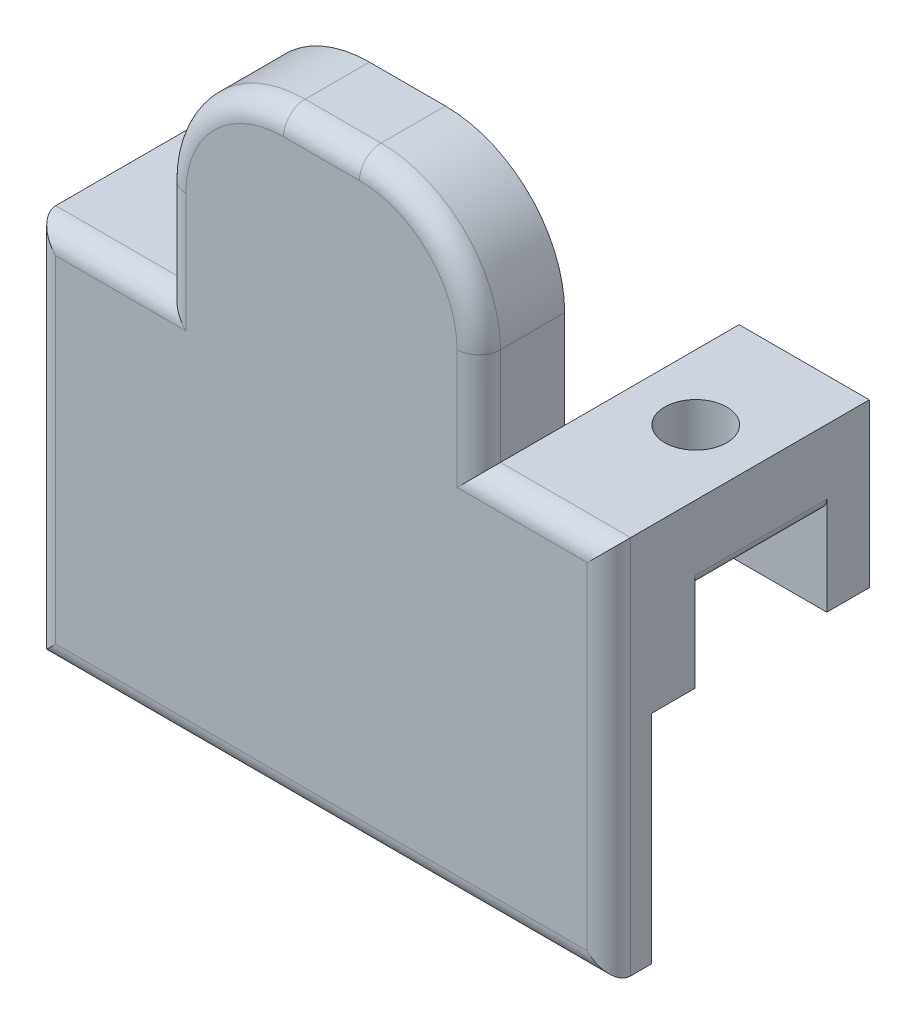
SolidWorks part; units mm, degrees
material "아크릴(내충격성)"
ref_plane "정면" through (0, 0, 0) normal (0, 0, 1) x (1, 0, 0)
ref_plane "윗면" through (0, 0, 0) normal (0, 1, 0) x (1, 0, 0)
ref_plane "우측면" through (0, 0, 0) normal (1, 0, 0) x (0, 0, -1)
sketch "스케치1" plane through (0, 0, 0) normal (0, 0, 1) x (1, 0, 0)
  line L1 (-26.5, 17.5) -> (26.5, 17.5)
  line L2 (-26.5, 17.5) -> (-26.5, -17.5)
  line L3 (-26.5, -17.5) -> (26.5, -17.5)
  line L4 (26.5, 17.5) -> (26.5, -17.5)
  line L5 (-26.5, 17.5) -> (26.5, -17.5) construction
  line L6 (-26.5, -17.5) -> (26.5, 17.5) construction
  point P0 (0, 0)
  dimension "D1" = 35
  dimension "D2" = 53
extrude "보스-돌출1" add sketch "스케치1" along normal blind 3.92
sketch "스케치2" plane through (0, 0, 3.92) normal (0, 0, 1) x (1, 0, 0)
  line L0 (26.5, 17.5) -> (-26.5, 17.5) construction
  line L1 (-26.5, 17.5) -> (-14.5, 17.5)
  line L2 (-26.5, 17.5) -> (-26.5, -9.5)
  line L3 (-26.5, -9.5) -> (-14.5, -9.5)
  line L4 (-14.5, 17.5) -> (-14.5, -9.5)
  line L5 (14.5, 17.5) -> (26.5, 17.5)
  line L6 (14.5, 17.5) -> (14.5, -9.5)
  line L7 (14.5, -9.5) -> (26.5, -9.5)
  line L8 (26.5, 17.5) -> (26.5, -9.5)
  line L9 (26.5, -17.5) -> (26.5, 17.5) construction
  dimension "D1" = 27
  dimension "D2" = 12
  dimension "D3" = 12
  dimension "D4" = 27
extrude "컷-돌출1" cut sketch "스케치2" against normal blind 4
sketch "스케치3" plane through (0, 0, 0) normal (0, 0, -1) x (-1, 0, 0)
  line L0 (0, 11) -> (0, -11) construction
  line L1 (-14.5, -9.5) -> (-26.5, -9.5)
  line L2 (-14.5, -9.5) -> (-14.5, -2.5)
  line L3 (-14.5, -2.5) -> (-26.5, -2.5)
  line L4 (-26.5, -9.5) -> (-26.5, -2.5)
  line L5 (26.5, -9.5) -> (26.5, -2.5)
  line L6 (14.5, -2.5) -> (26.5, -2.5)
  line L7 (14.5, -9.5) -> (14.5, -2.5)
  line L8 (14.5, -9.5) -> (26.5, -9.5)
  dimension "D1" = 12
  dimension "D2" = 7
extrude "보스-돌출2" add sketch "스케치3" along normal blind 16.08 and the other way through all
sketch "스케치4" plane through (0, -9.5, 0) normal (0, -1, 0) x (1, 0, 0)
  line L0 (-14.5, 0) -> (-14.5, -16.08) construction
  line L1 (-26.5, -16.08) -> (-14.5, -16.08)
  line L2 (-26.5, -16.08) -> (-26.5, -12.16)
  line L3 (-26.5, -12.16) -> (-14.5, -12.16)
  line L4 (-14.5, -16.08) -> (-14.5, -12.16)
  line L5 (26.5, -16.08) -> (14.5, -16.08) construction
  line L6 (14.5, -16.08) -> (26.5, -16.08)
  line L7 (14.5, -16.08) -> (14.5, -12.16)
  line L8 (14.5, -12.16) -> (26.5, -12.16)
  line L9 (26.5, -16.08) -> (26.5, -12.16)
  line L10 (26.5, 0) -> (26.5, -16.08) construction
  dimension "D1" = 3.92
  dimension "D2" = 3.92
extrude "보스-돌출3" add sketch "스케치4" along normal blind 8
sketch "스케치5" plane through (0, -2.5, 0) normal (0, 1, 0) x (1, 0, 0)
  line L0 (-26.5, -3.92) -> (-26.5, 16.08) construction
  line L1 (-26.5, -3.92) -> (-14.5, -3.92) construction
  line L2 (0, -11) -> (0, 11) construction
  circle A0 centre (-20.5, 6.08) radius 2.86
  circle A1 centre (20.5, 6.08) radius 2.86
  dimension "D2" = 5.72
  dimension "D1" = 6
  dimension "D3" = 10
extrude "컷-돌출2" cut sketch "스케치5" against normal through all
sketch "스케치6" plane through (0, 0, 3.92) normal (0, 0, 1) x (1, 0, 0)
  line L0 (14.5, 17.5) -> (-14.5, 17.5) construction
  line L1 (-14.5, -2.5) -> (-14.5, 17.5) construction
  circle A0 centre (0, 2.5) radius 6
  dimension "D3" = 12
  dimension "D1" = 15
  dimension "D2" = 14.5
extrude "컷-돌출3" cut sketch "스케치6" against normal blind 4
sketch "스케치7" plane through (0, 0, 3.92) normal (0, 0, 1) x (1, 0, 0)
  line L0 (-14.5, -2.5) -> (-26.5, -2.5)
  line L1 (-26.5, -2.5) -> (-26.5, -17.5)
  line L2 (-26.5, -17.5) -> (26.5, -17.5)
  line L3 (26.5, -17.5) -> (26.5, -2.5)
  line L4 (26.5, -2.5) -> (14.5, -2.5)
  line L5 (14.5, -2.5) -> (14.5, 17.5)
  line L6 (14.5, 17.5) -> (-14.5, 17.5)
  line L7 (-14.5, 17.5) -> (-14.5, -2.5)
extrude "보스-돌출4" add sketch "스케치7" along normal blind 4
sketch "스케치8" plane through (0, -17.5, 0) normal (0, -1, 0) x (1, 0, 0)
  line L0 (26.5, 7.92) -> (26.5, 0) construction
  line L1 (-26.5, 7.92) -> (26.5, 7.92)
  line L2 (-26.5, 7.92) -> (-26.5, 4)
  line L3 (-26.5, 4) -> (26.5, 4)
  line L4 (26.5, 7.92) -> (26.5, 4)
  dimension "D1" = 3.92
extrude "보스-돌출5" add sketch "스케치8" along normal blind 20
fillet "필렛1" radius 2.5 2 edges at (14.5, -9.5, -6.08) (-14.5, -9.5, -6.08)
fillet "필렛2" radius 11 2 edges at (14.5, 17.5, 3.96) (-14.5, 17.5, 3.96)
fillet "필렛3" radius 1 2 edges at (-26.5, -9.5, -6.08) (26.5, -9.5, -6.08)
fillet "필렛4" radius 2 10 edges at (20.5, -2.5, 7.92) (26.5, -20, 7.92) (0, -37.5, 7.92) (-26.5, -20, 7.92) (-20.5, -2.5, 7.92) (-14.5, 2, 7.92) (-11.2782, 14.2782, 7.92) (0, 17.5, 7.92) (11.2782, 14.2782, 7.92) (14.5, 2, 7.92)
